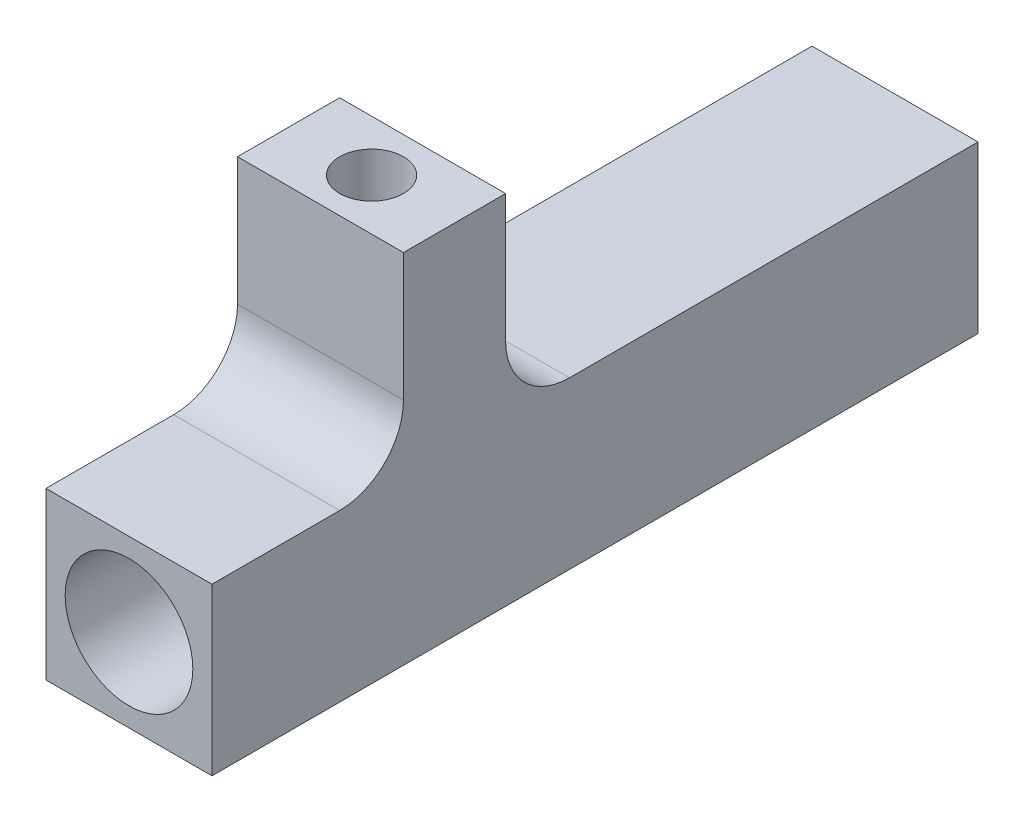
SolidWorks part; units mm, degrees
ref_plane "Front Plane" through (0, 0, 0) normal (0, 0, 1) x (1, 0, 0)
ref_plane "Top Plane" through (0, 0, 0) normal (0, 1, 0) x (1, 0, 0)
ref_plane "Right Plane" through (0, 0, 0) normal (1, 0, 0) x (0, 0, -1)
sketch "Sketch1" plane through (0, 0, 0) normal (0, 0, 1) x (1, 0, 0)
  line L1 (-13, -13) -> (13, -13)
  line L2 (-13, -13) -> (-13, 13)
  line L3 (-13, 13) -> (13, 13)
  line L4 (13, -13) -> (13, 13)
  line L5 (-13, -13) -> (13, 13) construction
  line L6 (-13, 13) -> (13, -13) construction
  circle A0 centre (0, 0) radius 10
  dimension "D1" = 13
  dimension "D3" = 20
  dimension "D2" = 13
sketch "Sketch2" plane through (0, 0, 0) normal (1, 0, 0) x (0, 0, -1)
  line L0 (0, 13) -> (0, -13) construction
  line L2 (36, 13) -> (100, 13)
  line L5 (0, -13) -> (100, -13)
  line L6 (100, 13) -> (100, -13)
  line L8 (10, 23) -> (10, 43)
  line L9 (10, 43) -> (26, 43)
  line L10 (26, 23) -> (26, 43)
  line L11 (0, 13) -> (36, 13) construction
  line L13 (0, 13) -> (-20, 13)
  line L15 (0, -13) -> (-20, -13)
  line L16 (-20, 13) -> (-20, -13)
  arc A0 (0, 13) -> (10, 23) centre (0, 23) ccw
  arc A1 (36, 13) -> (26, 23) centre (36, 23) cw
  point P0 (0, 13)
  point P14 (0, 0)
  dimension "D3" = 10
  dimension "D4" = 10
  dimension "D6" = 20
  dimension "D1" = 100
  dimension "D2" = 30
  dimension "D5" = 16
  dimension "D7" = 26
extrude "Boss-Extrude1" add sketch "Sketch2" along normal up to vertex (13 mm away) and the other way up to vertex (13 mm away) up to point (13, 13, 0) other way up to point (-13, 13, 0)
extrude "Cut-Extrude1" cut sketch "Sketch1" against normal up to surface and the other way up to surface contours A0 up to face at (0, 0, -100) other way up to face at (0, 0, 20)
sketch "Sketch3" plane through (0, 43, 0) normal (0, 1, 0) x (1, 0, 0)
  line L0 (-13, 26) -> (13, 10) construction
  line L1 (13, 26) -> (-13, 10) construction
  circle A0 centre (0, 18) radius 5
  dimension "D1" = 10
extrude "Cut-Extrude2" cut sketch "Sketch3" against normal up to surface (33 mm away)
